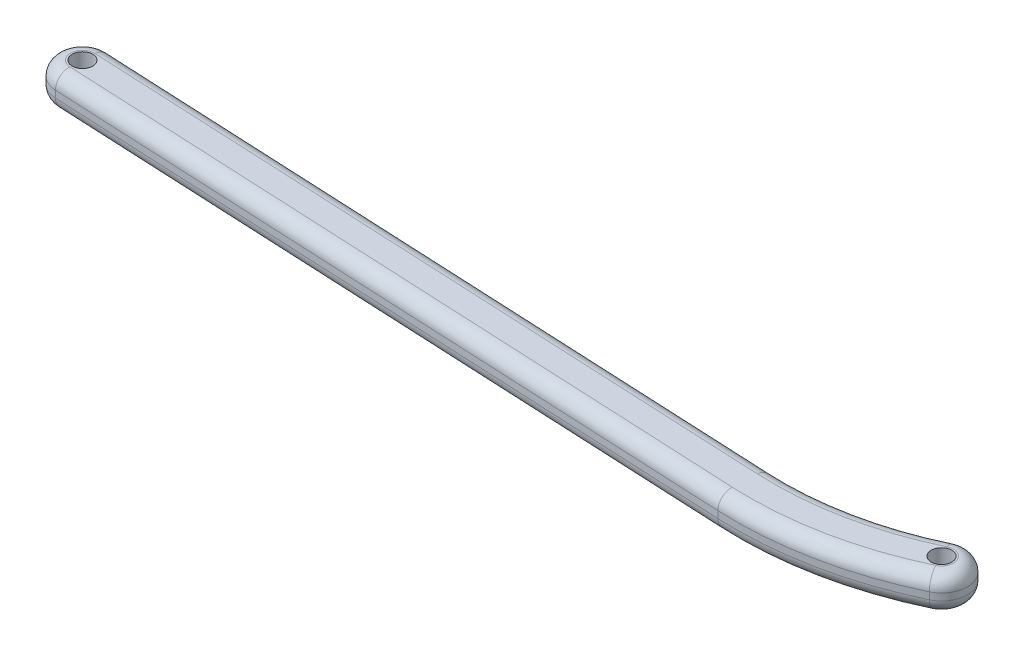
SolidWorks part; units mm, degrees
material "ABS PC"
ref_plane "Alzado" through (0, 0, 0) normal (1, 0, 0) x (0, 1, 0)
ref_plane "Planta" through (0, 0, 0) normal (0, 0, 1) x (0, 1, 0)
ref_plane "Vista lateral" through (0, 0, 0) normal (0, 1, 0) x (-1, 0, 0)
sketch "Croquis1" plane through (0, 0, 0) normal (0, 1, 0) x (-1, 0, 0)
  line L0 (0, 0) -> (250, 0) construction
  line L1 (47.6688, 9.5771) -> (250, 0) construction
  line L2 (48.0235, 17.0687) -> (250.3546, 7.4916)
  line L3 (47.3142, 2.0855) -> (249.6454, -7.4916)
  line L4 (250, 0) -> (47.6688, 9.5771) construction
  line L9 (125, -7.5) -> (125, 0) construction
  line L10 (0, 0) -> (42.9408, -90.3111) construction
  line L11 (42.9408, -90.3111) -> (47.6688, 9.5771) construction
  circle A0 centre (0, 0) radius 3
  circle A1 centre (250, 0) radius 3
  arc A2 (3.2206, -6.7733) -> (47.3142, 2.0855) centre (42.9408, -90.3111) cw
  arc A16 (249.6454, -7.4916) -> (250.3546, 7.4916) centre (250, 0) ccw
  arc A17 (0, 0) -> (47.6688, 9.5771) centre (42.9408, -90.3111) cw construction
  arc A20 (0, 0) -> (47.6688, 9.5771) centre (42.9408, -90.3111) cw construction
  arc A25 (-3.2206, 6.7733) -> (3.2206, -6.7733) centre (0, 0) ccw
  arc A27 (-3.2206, 6.7733) -> (48.0235, 17.0687) centre (42.9408, -90.3111) cw
  arc A28 (3.2206, -6.7733) -> (47.3142, 2.0855) centre (42.9408, -90.3111) cw construction
  point P12 (189.4945, 12.5454)
  point P24 (58.428, 23.6733)
  dimension "D3" = 6
  dimension "D2" = 100
  dimension "D4" = 7.5
  dimension "D1" = 250
  dimension "D5" = 2.71
extrude "Saliente-Extruir1" add sketch "Croquis1" along normal mid plane 10
fillet "Redondeo7" radius 4 12 edges at (-149.189, 5, 12.2802) (-257.4916, 5, -0.3546) (-148.4798, 5, -2.7031) (6.7733, 5, -3.2206) (-149.189, -5, 12.2802) (-257.4916, -5, -0.3546) (-148.4798, -5, -2.7031) (6.7733, -5, -3.2206) (-21.7662, -5, 15.0829) (-24.7208, -5, 0.3768) (-21.7662, 5, 15.0829) (-24.7208, 5, 0.3768)
equation "\"L1\"=250"
equation "\"ancho\"= 15"
equation "\"esp\"= 10"
equation "\"agujeros\"= 6"
equation "\"L2\"=260"
equation "\"D1@Croquis1\"=\"L1\""
equation "\"D3@Croquis1\"=\"agujeros\""
equation "\"D1@Saliente-Extruir1\"=\"esp\""
